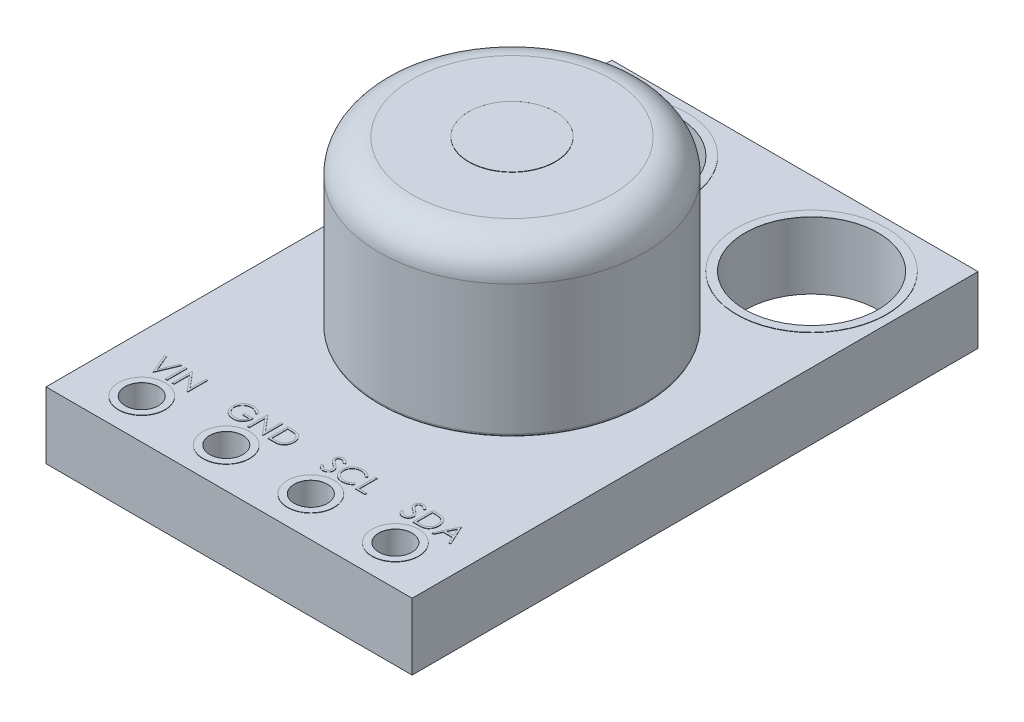
SolidWorks part; units mm, degrees
ref_plane "Plano frontal" through (0, 0, 0) normal (0, 0, 1) x (1, 0, 0)
ref_plane "Plano superior" through (0, 0, 0) normal (0, 1, 0) x (1, 0, 0)
ref_plane "Plano direito" through (0, 0, 0) normal (1, 0, 0) x (0, 0, -1)
sketch "Esboço1" plane through (0, 0, 0) normal (0, 1, 0) x (1, 0, 0)
  line L1 (-13.4472, -15.5399) -> (-2.4472, -15.5399)
  line L2 (-13.4472, -15.5399) -> (-13.4472, -32.5399)
  line L3 (-13.4472, -32.5399) -> (-2.4472, -32.5399)
  line L4 (-2.4472, -15.5399) -> (-2.4472, -32.5399)
extrude "Ressalto-extrusão1" add sketch "Esboço1" along normal blind 2
sketch "Esboço2" plane through (0, 2, 0) normal (0, 1, 0) x (1, 0, 0)
  line L1 (-13.4472, -32.5399) -> (-2.4472, -32.5399) construction
  line L2 (-2.4472, -15.5399) -> (-13.4472, -15.5399) construction
  line L3 (-2.4472, -32.5399) -> (-2.4472, -15.5399) construction
  line L5 (-13.4472, -15.5399) -> (-13.4472, -32.5399) construction
  circle A0 centre (-7.9472, -24.0399) radius 4
  dimension "D1" = 8
  dimension "D2" = 8.5
  dimension "D3" = 8.5
  dimension "D4" = 5.5
  dimension "D5" = 5.5
extrude "Ressalto-extrusão2" add sketch "Esboço2" along normal blind 5 separate body
fillet "Filete1" radius 1 1 edges at (-7.9472, 7, 28.0399)
sketch "Esboço3" plane through (0, 2, 0) normal (0, 1, 0) x (1, 0, 0)
  line L0 (-2.4472, -32.5399) -> (-2.4472, -15.5399) construction
  line L2 (-2.4472, -15.5399) -> (-13.4472, -15.5399) construction
  line L3 (-13.4472, -15.5399) -> (-13.4472, -32.5399) construction
  circle A0 centre (-11.7572, -31.3535) radius 0.5
  circle A1 centre (-9.2172, -31.3535) radius 0.5
  circle A2 centre (-6.6772, -31.3535) radius 0.5
  circle A3 centre (-4.1372, -31.3535) radius 0.5
  circle A4 centre (-10.9472, -18.0399) radius 2
  circle A5 centre (-4.9472, -18.0399) radius 2
  dimension "D1" = 1
  dimension "D2" = 2.54
  dimension "D3" = 2.54
  dimension "D4" = 2.54
  dimension "D5" = 1.69
  dimension "D6" = 2.5
  dimension "D7" = 2.5
  dimension "D8" = 2.5
  dimension "D9" = 2.5
sketch "Esboço4" plane through (0, 7, 0) normal (0, 1, 0) x (1, 0, 0)
  circle A0 centre (-7.9472, -24.0399) radius 1.3
extrude "Ressalto-extrusão3" add sketch "Esboço4" along normal blind 0.01 separate body
sketch "Esboço5" plane through (0, 2, 0) normal (0, 1, 0) x (1, 0, 0)
  circle A0 centre (-11.7572, -31.3535) radius 0.7
  circle A1 centre (-9.2172, -31.3535) radius 0.7
  circle A2 centre (-6.6772, -31.3535) radius 0.7
  circle A3 centre (-4.1372, -31.3535) radius 0.7
  circle A4 centre (-10.9472, -18.0399) radius 2.25
  circle A5 centre (-4.9472, -18.0399) radius 2.25
extrude "Ressalto-extrusão4" add sketch "Esboço5" along normal blind 0.01 separate body
extrude "Corte-extrusão2" cut sketch "Esboço3" against normal blind 25 and the other way blind 25
fillet "Filete3" radius 0.1 1 edges at (-7.9472, 2, 28.0399)
fillet "Filete4" radius 0.001 1 edges at (-7.9472, 7.01, 25.3399)
sketch "Esboço6" plane through (0, 2, 0) normal (0, 1, 0) x (1, 0, 0)
  text T0 "VIN    GND    SCL    SDA" font "Century Gothic" height 0.6
extrude "Ressalto-extrusão5" add sketch "Esboço6" along normal blind 0.01 separate body
